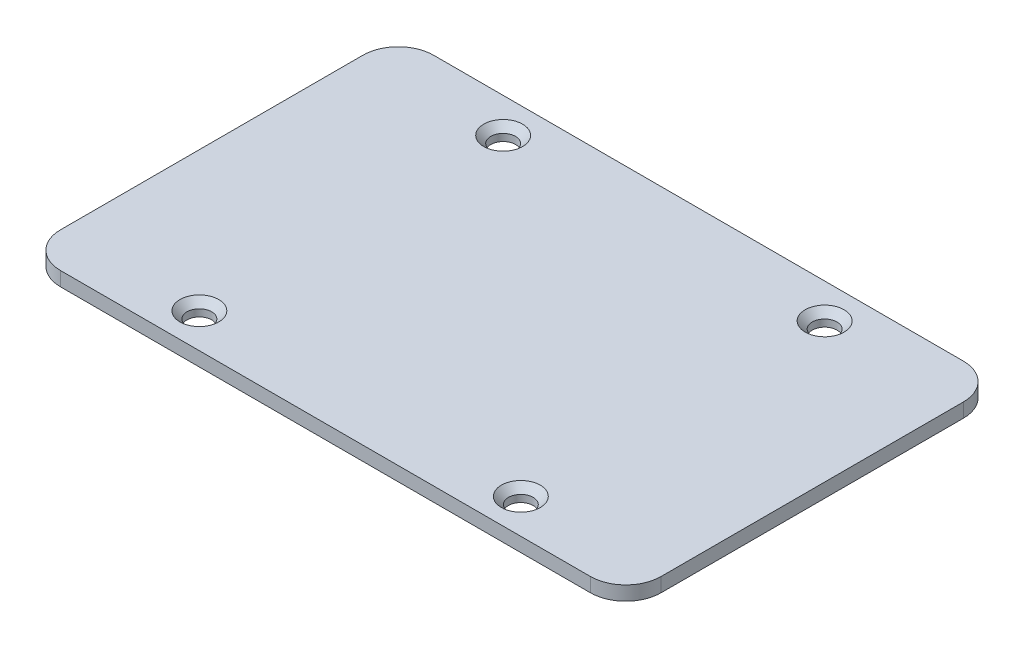
SolidWorks part; units mm, degrees
material "Thornel Mat VMA"
ref_plane "Front Plane" through (0, 0, 0) normal (0, 0, 1) x (1, 0, 0)
ref_plane "Top Plane" through (0, 0, 0) normal (0, 1, 0) x (1, 0, 0)
ref_plane "Right Plane" through (0, 0, 0) normal (1, 0, 0) x (0, 0, -1)
sketch "Sketch1" plane through (0, 0, 0) normal (0, 1, 0) x (1, 0, 0)
  line L1 (-42.5, 26.4) -> (42.5, 26.4)
  line L2 (-42.5, 26.4) -> (-42.5, -26.4)
  line L3 (-42.5, -26.4) -> (42.5, -26.4)
  line L4 (42.5, 26.4) -> (42.5, -26.4)
  line L5 (-42.5, 26.4) -> (42.5, -26.4) construction
  line L6 (-42.5, -26.4) -> (42.5, 26.4) construction
  point P0 (0, 0)
  dimension "D1" = 52.8
  dimension "D2" = 85
extrude "Boss-Extrude1" add sketch "Sketch1" along normal mid plane 2
sketch "Sketch2" plane through (0, 1, 0) normal (0, 1, 0) x (1, 0, 0)
  circle A0 centre (-22.75, 21.5) radius 1.75
  circle A1 centre (22.75, 21.5) radius 1.75
  circle A2 centre (22.75, -21.5) radius 1.75
  circle A3 centre (-22.75, -21.5) radius 1.75
  point P8 (0, 0)
  point P10 (0, 0)
  point P11 (0, 0)
  point P12 (0, 0)
  dimension "D1" = 3.5
  dimension "D2" = 21.5
  dimension "D4" = 43
  dimension "D3" = 22.75
  dimension "D5" = 45.5
extrude "Cut-Extrude1" cut sketch "Sketch2" against normal blind 2
chamfer "Chamfer1" distance 1 angle 45 4 edges at (22.75, 1, -19.75) (22.75, 1, 23.25) (-22.75, 1, 23.25) (-22.75, 1, -19.75)
fillet "Fillet2" radius 5 4 edges at (42.5, 0, -26.4) (42.5, 0, 26.4) (-42.5, 0, 26.4) (-42.5, 0, -26.4)
